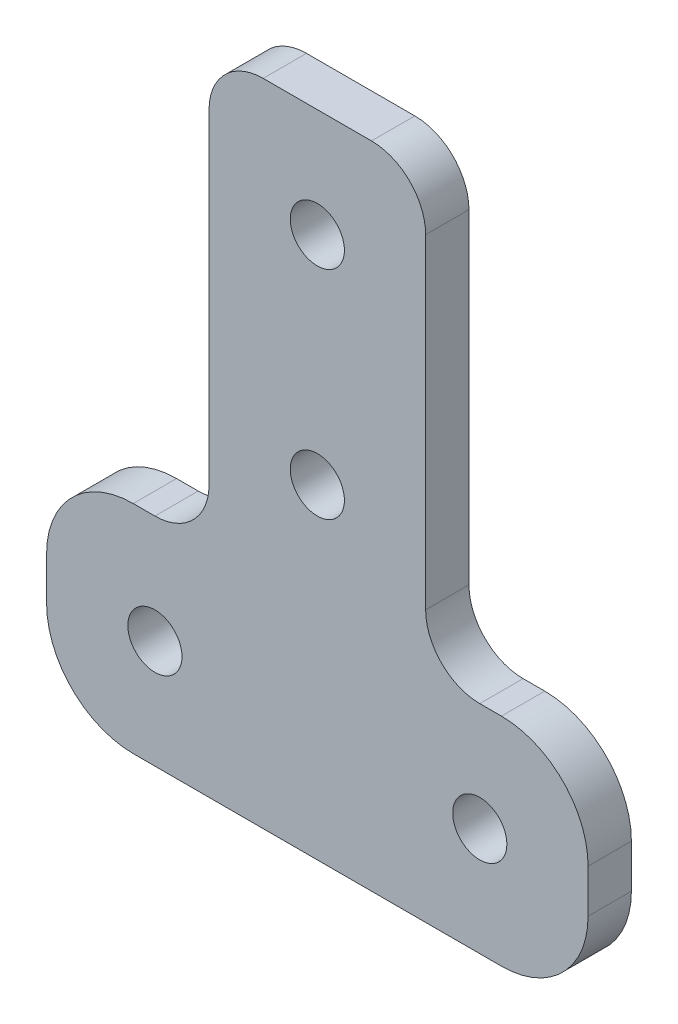
SolidWorks part; units mm, degrees
material "Thornel Mat VMA"
ref_plane "前视基准面" through (0, 0, 0) normal (0, 0, 1) x (1, 0, 0)
ref_plane "上视基准面" through (0, 0, 0) normal (0, 1, 0) x (1, 0, 0)
ref_plane "右视基准面" through (0, 0, 0) normal (1, 0, 0) x (0, 0, -1)
sketch "Sketch1" plane through (0, 0, 0) normal (0, 0, 1) x (1, 0, 0)
  line L0 (0, 0) -> (0, 60) construction
  line L1 (-10, 60) -> (10, 60)
  line L2 (10, 60) -> (10, 20)
  line L3 (10, 20) -> (25, 20)
  line L4 (25, 20) -> (25, 0)
  line L5 (25, 0) -> (-25, 0)
  line L6 (-25, 20) -> (-25, 0)
  line L7 (-10, 20) -> (-25, 20)
  line L8 (-10, 60) -> (-10, 20)
  circle A0 centre (0, 50) radius 2.5
  circle A1 centre (0, 30) radius 2.5
  circle A2 centre (15, 10) radius 2.5
  circle A3 centre (-15, 10) radius 2.5
  dimension "D8" = 5
  dimension "D9" = 5
  dimension "D10" = 5
  dimension "D11" = 5
  dimension "D14" = 10
  dimension "D1" = 60
  dimension "D2" = 25
  dimension "D3" = 10
  dimension "D4" = 20
  dimension "D5" = 10
  dimension "D6" = 30
  dimension "D7" = 20
  dimension "D12" = 15
  dimension "D13" = 15
extrude "Boss-Extrude1" add sketch "Sketch1" along normal blind 4
fillet "Fillet1" radius 5 4 edges at (-10, 60, 2) (10, 60, 2) (10, 20, 2) (-10, 20, 2)
fillet "Fillet2" radius 8 4 edges at (25, 0, 2) (25, 20, 2) (-25, 0, 2) (-25, 20, 2)
